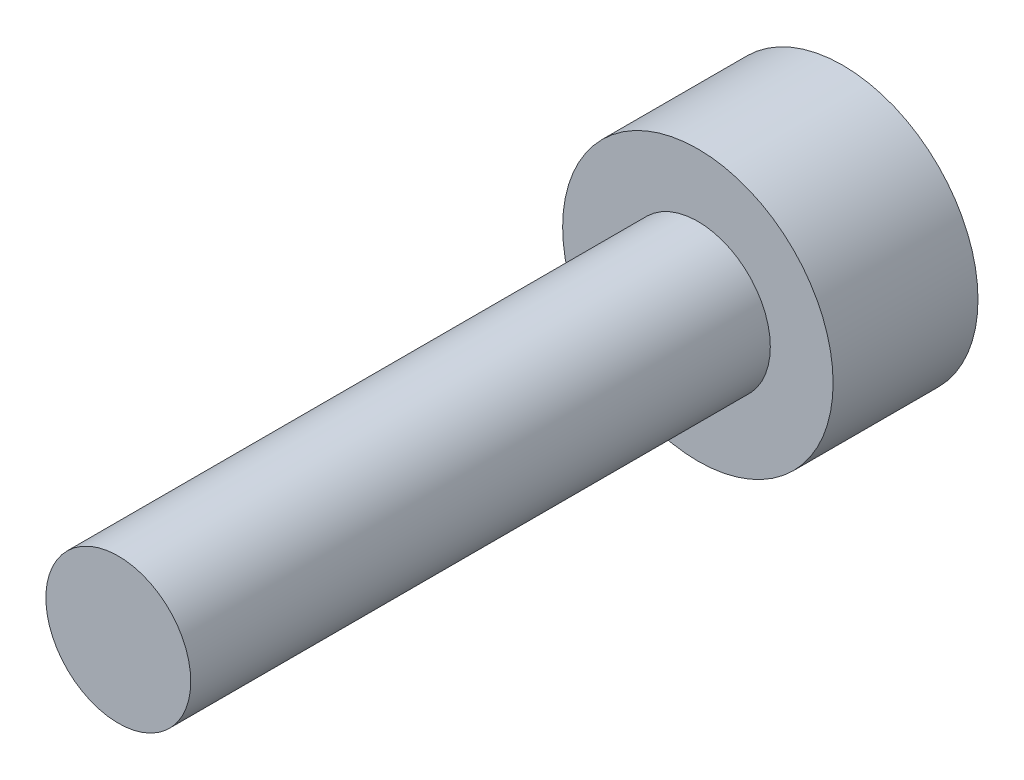
SolidWorks part; units mm, degrees
ref_plane "Front Plane" through (0, 0, 0) normal (0, 0, 1) x (1, 0, 0)
ref_plane "Top Plane" through (0, 0, 0) normal (0, 1, 0) x (1, 0, 0)
ref_plane "Right Plane" through (0, 0, 0) normal (1, 0, 0) x (0, 0, -1)
sketch "Sketch1" plane through (0, 0, 0) normal (0, 0, 1) x (1, 0, 0)
  circle A0 centre (0, 0) radius 2.8
extrude "Head" add sketch "Sketch1" along normal blind 3 from offset 3
sketch "Sketch2" plane through (0, 0, 0) normal (0, 0, 1) x (1, 0, 0)
  circle A0 centre (0, 0) radius 1.5
extrude "Shank" add sketch "Sketch2" along normal blind 12
sketch "Sketch3" plane through (0, 0, 0) normal (0, 0, 1) x (1, 0, 0)
  line L0 (1.25, 0.7217) -> (0, 1.4434)
  line L1 (0, 1.4434) -> (-1.25, 0.7217)
  line L2 (-1.25, 0.7217) -> (-1.25, -0.7217)
  line L3 (-1.25, -0.7217) -> (0, -1.4434)
  line L4 (0, -1.4434) -> (1.25, -0.7217)
  line L5 (1.25, -0.7217) -> (1.25, 0.7217)
extrude "Hex socket" cut sketch "Sketch3" along normal blind 1.8 from offset 3.2
